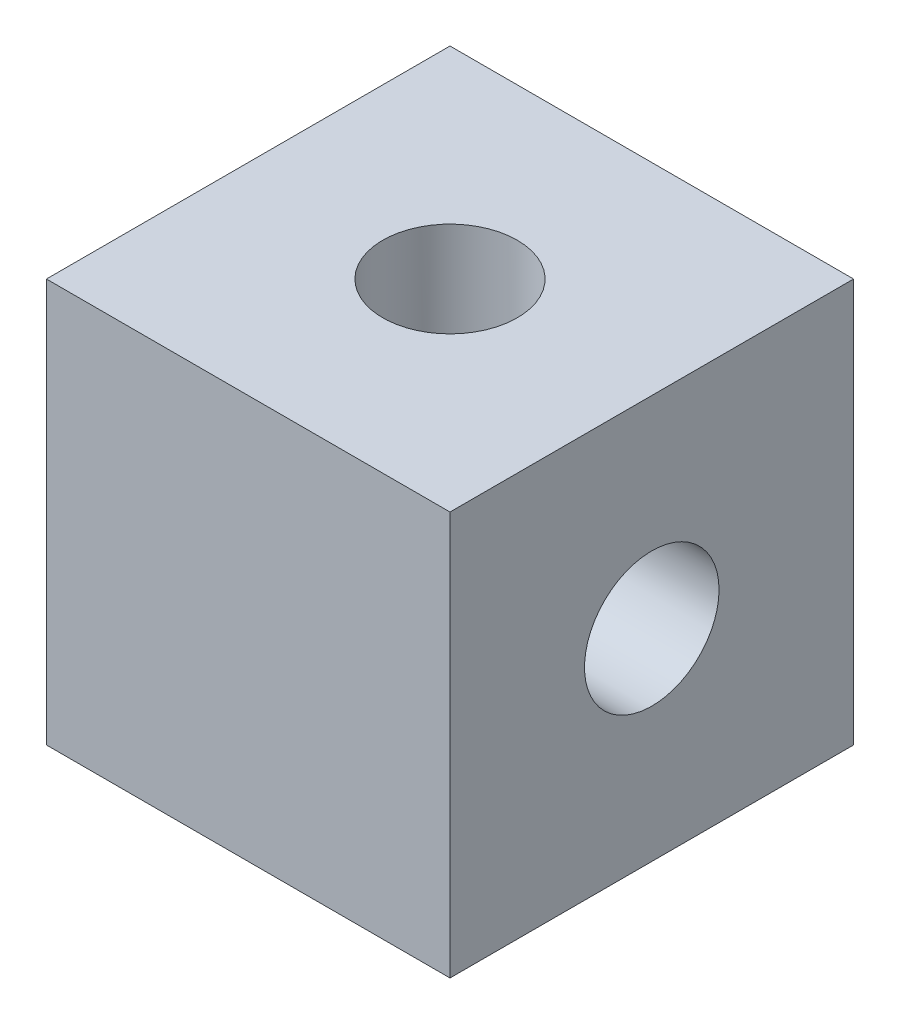
SolidWorks part; units mm, degrees
ref_plane "Front Plane" through (0, 0, 0) normal (0, 0, 1) x (1, 0, 0)
ref_plane "Top Plane" through (0, 0, 0) normal (0, 1, 0) x (1, 0, 0)
ref_plane "Right Plane" through (0, 0, 0) normal (1, 0, 0) x (0, 0, -1)
sketch "Sketch1" plane through (0, 0, 0) normal (0, 1, 0) x (1, 0, 0)
  line L0 (-37.5, -37.5) -> (37.5, -37.5)
  line L1 (-37.5, -37.5) -> (-37.5, 37.5)
  line L2 (37.5, -37.5) -> (37.5, 37.5)
  line L3 (-37.5, 37.5) -> (37.5, 37.5)
  line L4 (-37.5, -37.5) -> (37.5, 37.5) construction
  line L5 (37.5, -37.5) -> (-37.5, 37.5) construction
  point P1 (0, 0)
  dimension "D1" = 75
  dimension "D2" = 75
extrude "Boss-Extrude1" add sketch "Sketch1" along normal blind 75
sketch "Sketch2" plane through (0, 0, 0) normal (0, -1, 0) x (-1, 0, 0)
  circle A0 centre (0, 0) radius 12.5
  dimension "D1" = 25
extrude "Cut-Extrude1" cut sketch "Sketch2" against normal through all
sketch "Sketch5" plane through (37.5, 0, 0) normal (1, 0, 0) x (0, 0, -1)
  line L0 (0, 0) -> (0, 75) construction
  line L1 (-37.5, 0) -> (37.5, 0) construction
  line L2 (-37.5, 75) -> (37.5, 75) construction
  line L3 (-37.5, 37.5) -> (37.5, 37.5) construction
  line L4 (-37.5, 75) -> (-37.5, 0) construction
  line L5 (37.5, 75) -> (37.5, 0) construction
  circle A0 centre (0, 37.5) radius 12.5
  dimension "D1" = 25
extrude "Cut-Extrude2" cut sketch "Sketch5" against normal through all
